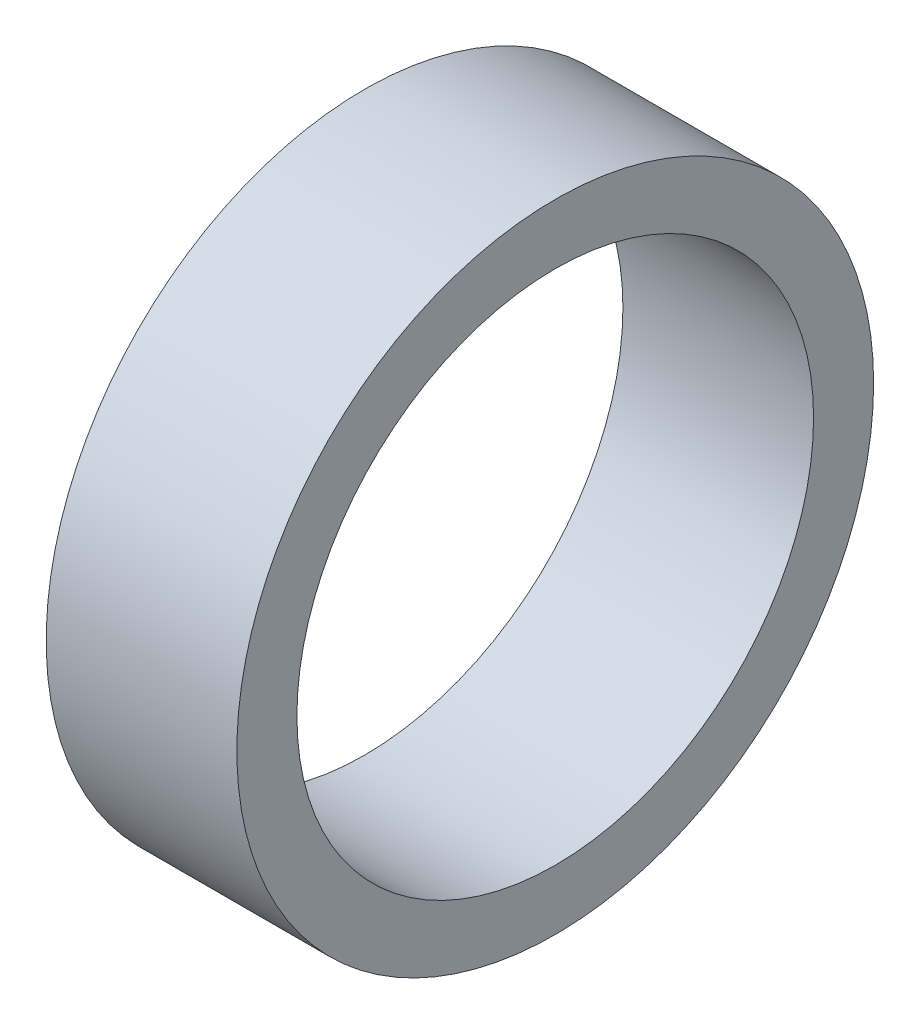
SolidWorks part; units mm, degrees
ref_plane "Front Plane" through (0, 0, 0) normal (0, 0, 1) x (1, 0, 0)
ref_plane "Top Plane" through (0, 0, 0) normal (0, 1, 0) x (1, 0, 0)
ref_plane "Right Plane" through (0, 0, 0) normal (1, 0, 0) x (0, 0, -1)
sketch "Sketch1" plane through (0, 0, 0) normal (1, 0, 0) x (0, 0, -1)
  circle A0 centre (0, 0) radius 27.1
  circle A1 centre (0, 0) radius 33.4
  dimension "D1" = 66.8
  dimension "D2" = 54.2
extrude "Boss-Extrude1" add sketch "Sketch1" along normal mid plane 20
